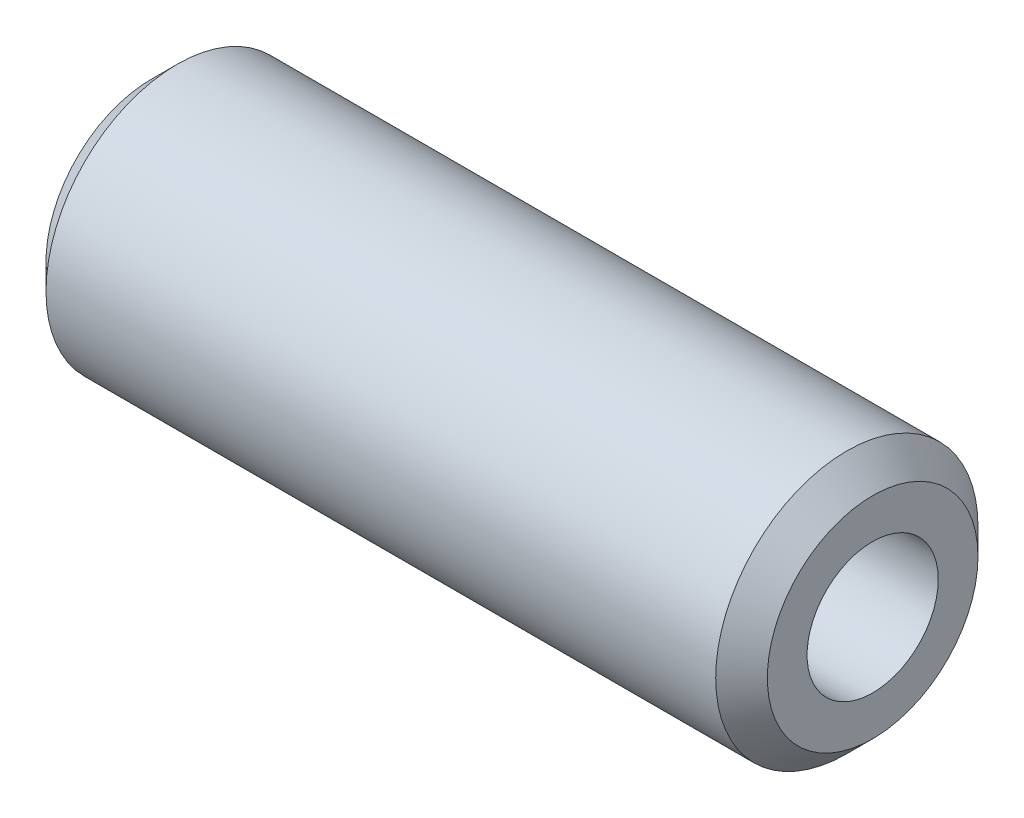
SolidWorks part; units mm, degrees
ref_plane "Front Plane" through (0, 0, 0) normal (1, 0, 0) x (0, 1, 0)
ref_plane "Top Plane" through (0, 0, 0) normal (0, 0, 1) x (0, 1, 0)
ref_plane "Right Plane" through (0, 0, 0) normal (0, 1, 0) x (-1, 0, 0)
sketch "Sketch1" plane through (0, 0, 0) normal (1, 0, 0) x (0, 1, 0)
  circle A0 centre (0, 0) radius 12.7
  circle A1 centre (0, 0) radius 6.35
  dimension "D1" = 25.4
  dimension "D2" = 12.7
extrude "Boss-Extrude1" add sketch "Sketch1" along normal mid plane 69.85
chamfer "Chamfer1" distance 2.5 angle 45 2 edges at (34.925, 0, -12.7) (-34.925, 0, -12.7)
